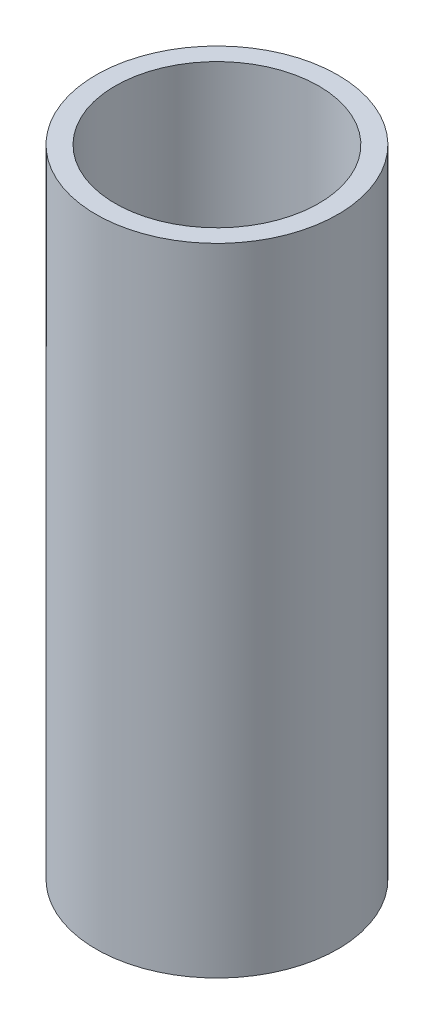
SolidWorks part; units mm, degrees
material " 12Х18Н10Т ГОСТ 4543-71"
ref_plane "Спереди" through (0, 0, 0) normal (0, 0, 1) x (1, 0, 0)
ref_plane "Сверху" through (0, 0, 0) normal (0, 1, 0) x (1, 0, 0)
ref_plane "Справа" through (0, 0, 0) normal (1, 0, 0) x (0, 0, -1)
sketch "Эскиз1" plane through (0, 0, 0) normal (0, 0, 1) x (1, 0, 0)
  line L0 (0, 0) -> (0, 62.8375) construction
  line L1 (-16, 0) -> (-16, 100)
  line L2 (-19, 0) -> (-19, 100)
  line L3 (-16, 100) -> (-19, 100)
  line L4 (-16, 0) -> (-19, 0)
  dimension "D1" = 32
  dimension "D2" = 100
  dimension "D3" = 3
revolve "Повернуть1" add sketch "Эскиз1" angle 360 about L0
